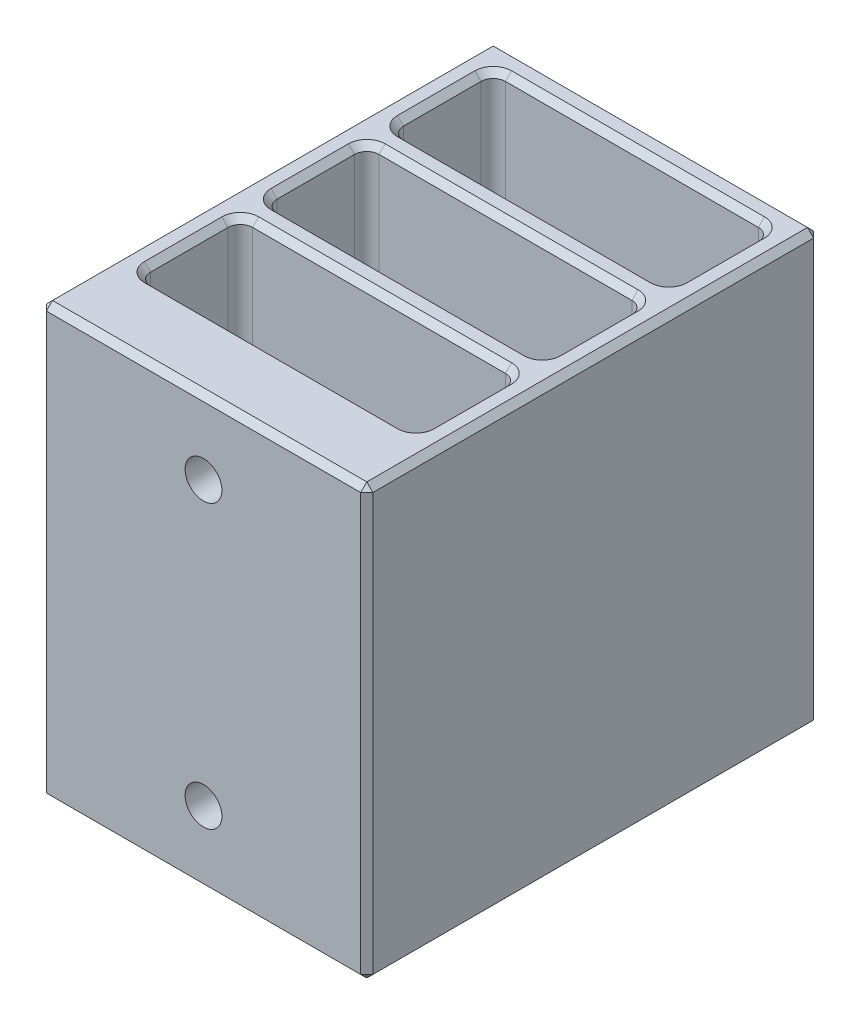
SolidWorks part; units mm, degrees
ref_plane "Front Plane" through (0, 0, 0) normal (0, 0, 1) x (1, 0, 0)
ref_plane "Top Plane" through (0, 0, 0) normal (0, 1, 0) x (1, 0, 0)
ref_plane "Right Plane" through (0, 0, 0) normal (1, 0, 0) x (0, 0, -1)
sketch "Sketch2" plane through (0, 0, 0) normal (0, 1, 0) x (1, 0, 0)
  line L7 (-11.3, -6.15) -> (11.3, -6.15)
  line L8 (-11.3, -6.15) -> (-11.3, -14.45)
  line L9 (-11.3, -14.45) -> (11.3, -14.45)
  line L10 (11.3, -6.15) -> (11.3, -14.45)
  line L11 (-11.3, 4.15) -> (11.3, 4.15)
  line L12 (-11.3, 4.15) -> (-11.3, -4.15)
  line L13 (-11.3, -4.15) -> (11.3, -4.15)
  line L14 (11.3, 4.15) -> (11.3, -4.15)
  line L15 (-11.3, 14.45) -> (11.3, 14.45)
  line L16 (-11.3, 14.45) -> (-11.3, 6.15)
  line L17 (-11.3, 6.15) -> (11.3, 6.15)
  line L18 (11.3, 14.45) -> (11.3, 6.15)
  line L20 (-13.3, 16.45) -> (13.3, 16.45)
  line L21 (-13.3, 16.45) -> (-13.3, -20.45)
  line L22 (-13.3, -20.45) -> (13.3, -20.45)
  line L23 (13.3, 16.45) -> (13.3, -20.45)
  point P0 (0, 0)
  point P18 (0, 0)
  point P21 (0, -20.45)
  point P22 (0, 4.15)
  point P23 (11.3, 0)
  dimension "D1" = 8.3
  dimension "D2" = 22.6
  dimension "D3" = 6
  dimension "D4" = 2
  dimension "D5" = 2
  dimension "D6" = 2
  dimension "D7" = 2
extrude "Boss-Extrude2" add sketch "Sketch2" along normal blind 35
fillet "Fillet1" radius 1 12 edges at (11.3, 17.5, 14.45) (-11.3, 17.5, 14.45) (-11.3, 17.5, 6.15) (11.3, 17.5, 6.15) (11.3, 17.5, 4.15) (11.3, 17.5, -4.15) (-11.3, 17.5, -4.15) (-11.3, 17.5, 4.15) (11.3, 17.5, -14.45) (11.3, 17.5, -6.15) (-11.3, 17.5, -14.45) (-11.3, 17.5, -6.15)
chamfer "Chamfer1" distance 0.5 angle 45 60 edges at (11.0071, 0, -14.1571) (11.3, 0, -10.3) (11.0071, 0, -6.4429) (0, 0, -6.15) (-11.0071, 0, -6.4429) (-11.3, 0, -10.3) (-11.0071, 0, -14.1571) (0, 0, -14.45) (11.0071, 0, 6.4429) (11.3, 0, 10.3) (11.0071, 0, 14.1571) (0, 0, 14.45) (-11.0071, 0, 14.1571) (-11.3, 0, 10.3) (-11.0071, 0, 6.4429) (0, 0, 6.15) (11.0071, 0, -3.8571) (11.3, 0, 0) (11.0071, 0, 3.8571) (0, 0, 4.15) (-11.0071, 0, 3.8571) (-11.3, 0, 0) (-11.0071, 0, -3.8571) (0, 0, -4.15) (13.3, 35, 2) (13.3, 0, 2) (0, 35, 20.45) (13.3, 17.5, 20.45) (0, 0, 20.45) (-13.3, 35, 2) (-13.3, 17.5, 20.45) (-13.3, 0, 2) (13.3, 17.5, -16.45) (0, 35, -16.45) (-13.3, 17.5, -16.45) (0, 0, -16.45) (0, 35, 6.15) (-11.0071, 35, 6.4429) (11.0071, 35, 6.4429) (-11.3, 35, 10.3) (11.3, 35, 10.3) (-11.0071, 35, 14.1571) (11.0071, 35, 14.1571) (0, 35, 14.45) (0, 35, -4.15) (-11.0071, 35, -3.8571) (11.0071, 35, -3.8571) (-11.3, 35, 0) (11.3, 35, 0) (-11.0071, 35, 3.8571) (11.0071, 35, 3.8571) (0, 35, 4.15) (11.3, 35, -10.3) (11.0071, 35, -14.1571) (11.0071, 35, -6.4429) (0, 35, -14.45) (0, 35, -6.15) (-11.0071, 35, -14.1571) (-11.0071, 35, -6.4429) (-11.3, 35, -10.3)
sketch "Sketch3" plane through (0, 0, 20.45) normal (0, 0, 1) x (1, 0, 0)
  line L0 (-12.8, 35) -> (12.8, 35) construction
  line L1 (12.8, 0) -> (-12.8, 0) construction
  circle A0 centre (0, 29) radius 1.5
  circle A1 centre (0, 6) radius 1.5
  dimension "D1" = 3
  dimension "D2" = 6
  dimension "D3" = 6
extrude "Cut-Extrude1" cut sketch "Sketch3" against normal up to next
